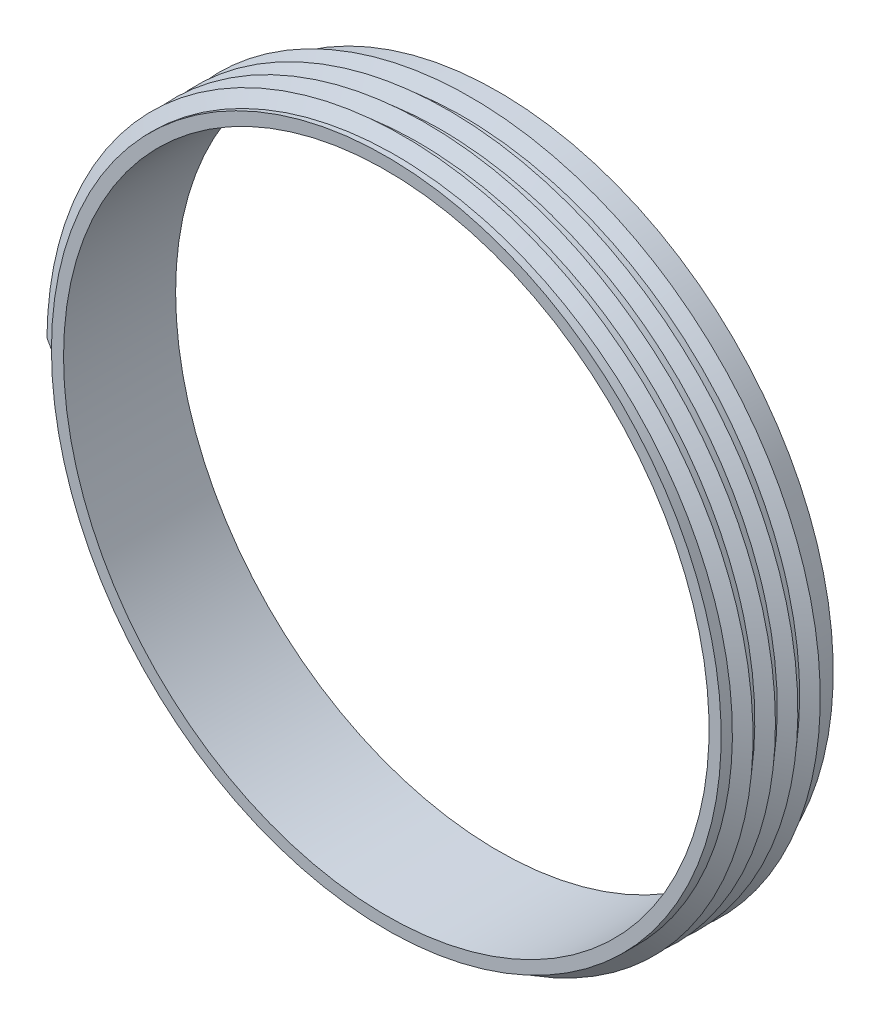
SolidWorks part; units mm, degrees
ref_plane "Front Plane" through (0, 0, 0) normal (0, 0, 1) x (1, 0, 0)
ref_plane "Top Plane" through (0, 0, 0) normal (0, 1, 0) x (1, 0, 0)
ref_plane "Right Plane" through (0, 0, 0) normal (1, 0, 0) x (0, 0, -1)
sketch "Sketch22" plane through (0, 0, 0) normal (0, 0, -1) x (-1, 0, 0)
  circle A0 centre (0, 0) radius 36
  circle A1 centre (0, 0) radius 37.35
  dimension "D1" = 1.35
  dimension "D2" = 72
extrude "Boss-Extrude6" add sketch "Sketch22" along normal blind 12.5
sketch "Sketch30" plane through (0, 0, 0) normal (0, 0, -1) x (-1, 0, 0)
  circle A0 centre (0, 0) radius 37.35
  circle A1 centre (0, 0) radius 37.35 construction
curve "Helix/Spiral1" pitch 2.5 height 10 turns 4
sketch "Sketch31" plane through (0, 0, 0) normal (0, 1, 0) x (1, 0, 0)
  line L0 (-37.35, 0) -> (-36.35, 0)
  line L1 (-37.35, 12.5) -> (-37.35, 0) construction
  line L2 (-36.35, 0) -> (-36.35, 1.8)
  line L3 (-36.35, 1.8) -> (-37.35, 1.8)
  line L4 (-37.35, 1.8) -> (-38.75, 0.9)
  line L5 (-38.75, 0.9) -> (-37.35, 0)
  line L7 (-38.75, 0.9) -> (-36.35, 0.9) construction
  line L8 (-37.35, 0) -> (37.35, 0) construction
  dimension "D1" = 1
  dimension "D2" = 1.8
  dimension "D3" = 2.4
  dimension "D4" = 1.4
sweep "Sweep1" add profiles "Sketch31" path "Helix/Spiral1"
